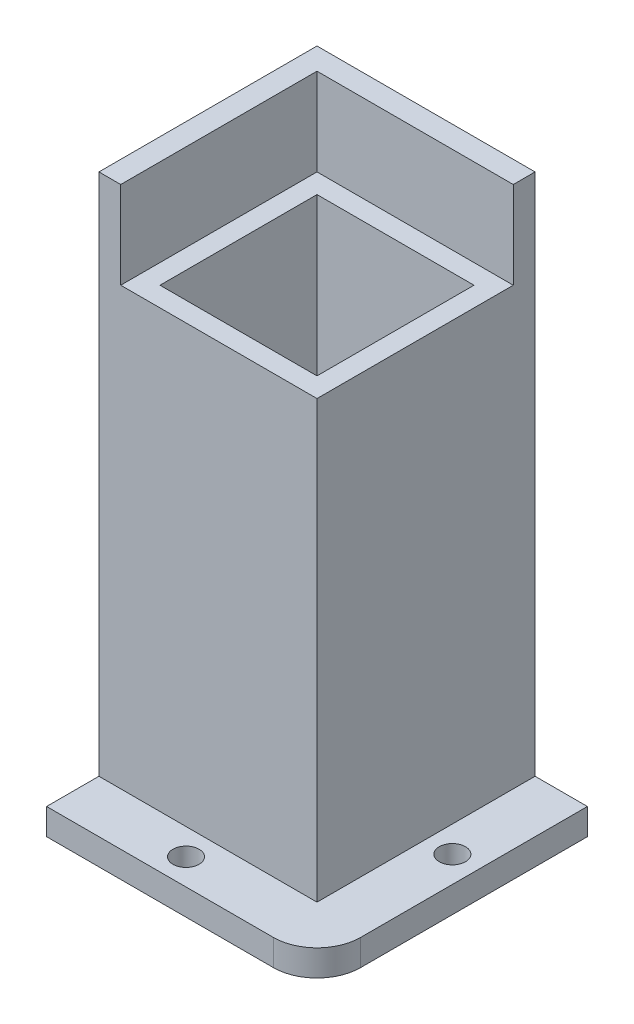
SolidWorks part; units mm, degrees
ref_plane "Front Plane" through (0, 0, 0) normal (0, 0, 1) x (1, 0, 0)
ref_plane "Top Plane" through (0, 0, 0) normal (0, 1, 0) x (1, 0, 0)
ref_plane "Right Plane" through (0, 0, 0) normal (1, 0, 0) x (0, 0, -1)
sketch "Sketch1" plane through (0, 0, 0) normal (0, 1, 0) x (1, 0, 0)
  line L1 (-12.5, 12.5) -> (12.5, 12.5)
  line L2 (-12.5, 12.5) -> (-12.5, -12.5)
  line L3 (-12.5, -12.5) -> (12.5, -12.5)
  line L4 (12.5, 12.5) -> (12.5, -12.5)
  line L5 (-12.5, 12.5) -> (12.5, -12.5) construction
  line L6 (-12.5, -12.5) -> (12.5, 12.5) construction
  point P0 (0, 0)
  dimension "D1" = 25
  dimension "D2" = 25
extrude "Boss-Extrude1" add sketch "Sketch1" along normal blind 63
sketch "Sketch2" plane through (0, 63, 0) normal (0, 1, 0) x (1, 0, 0)
  line L1 (12.5, -12.5) -> (-10, -12.5)
  line L2 (12.5, -12.5) -> (12.5, 10)
  line L3 (12.5, 10) -> (-10, 10)
  line L4 (-10, -12.5) -> (-10, 10)
  dimension "D1" = 22.5
  dimension "D2" = 22.5
extrude "Cut-Extrude2" cut sketch "Sketch2" against normal blind 10
sketch "Sketch4" plane through (0, 0, 0) normal (0, -1, 0) x (1, 0, 0)
  line L0 (0.5, 18.5) -> (0.468, 12.5) construction
  line L1 (-12.5, -12.5) -> (18.5, -12.5)
  line L2 (-12.5, -12.5) -> (-12.5, 18.5)
  line L3 (-12.5, 18.5) -> (13.5, 18.5)
  line L4 (18.5, -12.5) -> (18.5, 13.5)
  line L5 (12.5, 12.5) -> (-12.5, 12.5)
  line L6 (12.5, 12.5) -> (12.5, -12.5)
  line L7 (12.5, -12.5) -> (-12.5, -12.5)
  line L8 (-12.5, 12.5) -> (-12.5, -12.5)
  line L9 (12.5, 0) -> (18.5, -0.0379) construction
  line L10 (-12.5, 12.5) -> (12.5, 12.5) construction
  arc A0 (13.5, 18.5) -> (18.5, 13.5) centre (13.5, 13.5) cw
  circle A1 centre (0.484, 15.5) radius 1.5
  circle A2 centre (15.5, -0.0189) radius 1.5
  point P11 (18.5, 18.5)
  line M9 (12.5, -12.5) -> (12.5, 12.5)
  line M10 (12.5, 12.5) -> (-12.5, 12.5)
  dimension "D3" = 5
  dimension "D4" = 3
  dimension "D5" = 3
  dimension "D1" = 31
  dimension "D2" = 31
extrude "Boss-Extrude2" add sketch "Sketch4" against normal blind 3 contours L1 L4 L3 L2 M10 M9
sketch "Sketch5" plane through (0, 53, 0) normal (0, 1, 0) x (1, 0, 0)
  line L0 (-10, -1.25) -> (12.5, -1.25) construction
  line L1 (-10, 10) -> (-10, -12.5) construction
  line L2 (12.5, -12.5) -> (12.5, 10) construction
  line L4 (-7.75, 7.75) -> (10.25, 7.75)
  line L5 (-7.75, 7.75) -> (-7.75, -10.25)
  line L6 (-7.75, -10.25) -> (10.25, -10.25)
  line L7 (10.25, 7.75) -> (10.25, -10.25)
  line L8 (-7.75, 7.75) -> (10.25, -10.25) construction
  line L9 (-7.75, -10.25) -> (10.25, 7.75) construction
  point P6 (1.25, -1.25)
  dimension "D1" = 18
  dimension "D2" = 18
extrude "Cut-Extrude3" cut sketch "Sketch5" against normal blind 50
